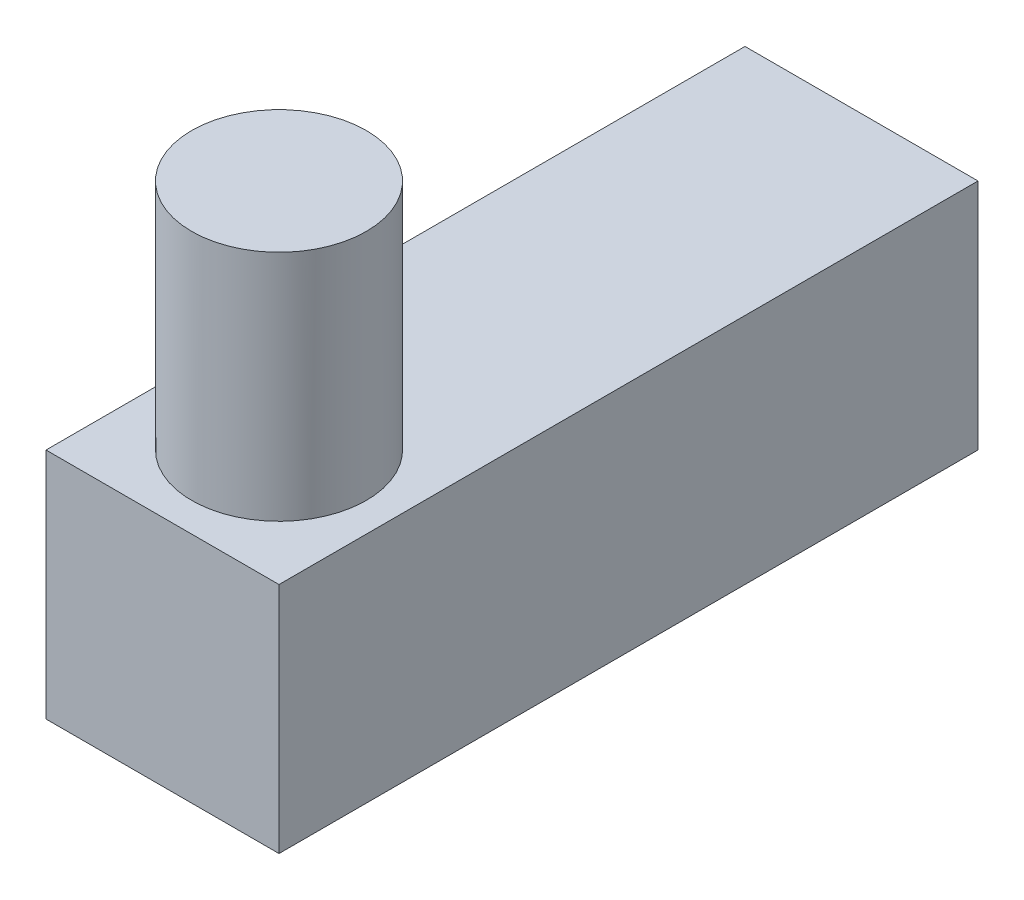
SolidWorks part; units mm, degrees
ref_plane "Front Plane" through (0, 0, 0) normal (0, 0, 1) x (1, 0, 0)
ref_plane "Top Plane" through (0, 0, 0) normal (0, 1, 0) x (1, 0, 0)
ref_plane "Right Plane" through (0, 0, 0) normal (1, 0, 0) x (0, 0, -1)
sketch "Sketch1" plane through (0, 0, 0) normal (0, 1, 0) x (1, 0, 0)
  line L1 (0, 0) -> (101.6, 0)
  line L2 (0, 0) -> (0, 304.8)
  line L3 (0, 304.8) -> (101.6, 304.8)
  line L4 (101.6, 0) -> (101.6, 304.8)
extrude "Boss-Extrude1" add sketch "Sketch1" along normal blind 101.6
sketch "Sketch2" plane through (0, 101.6, 0) normal (0, 1, 0) x (1, 0, 0)
  circle A0 centre (50.8, 50.8) radius 38.1
extrude "Boss-Extrude2" add sketch "Sketch2" along normal blind 101.6
